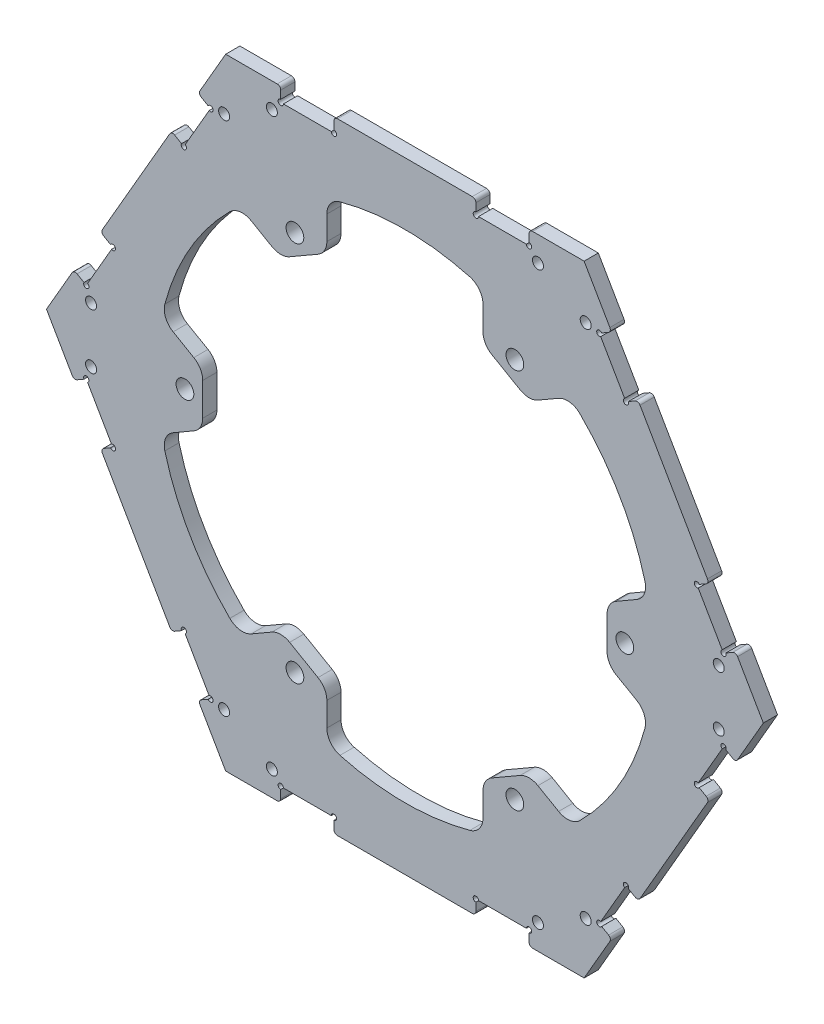
SolidWorks part; units mm, degrees
other "Markup1"
sketch "Sketch62" plane through (-128.5, -128.5, 146.8) normal (-0.0672, -0.6619, 0.7466) x (0.996, 0, 0.0896)
other "Markup2"
sketch "Sketch87" plane through (-128.5, 200.1498, -230) normal (-0.7911, 0.6051, -0.0891) x (-0.112, 0, 0.9937)
ref_plane "Front" through (0, 0, 0) normal (0, 0, 1) x (1, 0, 0)
ref_plane "Top" through (0, 0, 0) normal (0, 1, 0) x (1, 0, 0)
ref_plane "Right" through (0, 0, 0) normal (1, 0, 0) x (0, 0, -1)
sketch "Sketch80" plane through (0, 0, 0) normal (0, 0, -1) x (-1, 0, 0)
  line L0 (-68.551, 14.169) -> (-57, 7.5)
  line L1 (-57, 7.5) -> (-57, -7.5)
  line L2 (0, 0) -> (-81.4055, 0) construction
  line L3 (-68.551, -14.169) -> (-57, -7.5)
  line L4 (-22.0048, 66.4514) -> (-22.0048, 53.1134)
  line L5 (-22.0048, 53.1134) -> (-34.9952, 45.6134)
  line L7 (106.8098, 0) -> (53.4049, 92.5)
  line L8 (53.4049, 92.5) -> (-53.4049, 92.5)
  line L9 (-53.4049, 92.5) -> (-106.8098, 0)
  line L10 (-106.8098, 0) -> (-53.4049, -92.5)
  line L11 (-53.4049, -92.5) -> (53.4049, -92.5)
  line L18 (-46.5462, 52.2824) -> (-34.9952, 45.6134)
  line L19 (46.5462, 52.2824) -> (34.9952, 45.6134)
  line L20 (34.9952, 45.6134) -> (22.0048, 53.1134)
  line L21 (22.0048, 66.4514) -> (22.0048, 53.1134)
  line L22 (68.551, -14.169) -> (57, -7.5)
  line L23 (57, -7.5) -> (57, 7.5)
  line L24 (68.551, 14.169) -> (57, 7.5)
  line L25 (22.0048, -66.4514) -> (22.0048, -53.1134)
  line L26 (22.0048, -53.1134) -> (34.9952, -45.6134)
  line L27 (46.5462, -52.2824) -> (34.9952, -45.6134)
  line L28 (-46.5462, -52.2824) -> (-34.9952, -45.6134)
  line L29 (-34.9952, -45.6134) -> (-22.0048, -53.1134)
  line L30 (-22.0048, -66.4514) -> (-22.0048, -53.1134)
  line L31 (53.4049, -92.5) -> (106.8098, 0)
  arc A0 (-68.551, -14.169) -> (-46.5462, -52.2824) centre (0, 0) ccw
  arc A1 (-46.5462, 52.2824) -> (-68.551, 14.169) centre (0, 0) ccw
  arc A2 (22.0048, 66.4514) -> (-22.0048, 66.4514) centre (0, 0) ccw
  arc A3 (68.551, 14.169) -> (46.5462, 52.2824) centre (0, 0) ccw
  arc A4 (46.5462, -52.2824) -> (68.551, -14.169) centre (0, 0) ccw
  arc A5 (-22.0048, -66.4514) -> (22.0048, -66.4514) centre (0, 0) ccw
  circle A18 centre (0, 0) radius 92.5 construction
  circle A19 centre (-62, 0) radius 2.5
  circle A20 centre (-31, 53.6936) radius 2.5
  circle A21 centre (31, 53.6936) radius 2.5
  circle A22 centre (62, 0) radius 2.5
  circle A23 centre (31, -53.6936) radius 2.5
  circle A24 centre (-31, -53.6936) radius 2.5
  point P16 (-57, 0)
  point P47 (0, 0)
  dimension "D2" = 140
  dimension "D1" = 185
  dimension "D7" = 5
  dimension "D9" = 62
  dimension "D3" = 120
  dimension "D4" = 57
  dimension "D5" = 15
  dimension "D6" = 6
  dimension "D8" = 6
extrude "Boss-Extrude22" add sketch "Sketch80" along normal blind 4 separate body
sketch "Sketch88" plane through (0, 0, -4) normal (0, 0, -1) x (-1, 0, 0)
  line L0 (0, 0) -> (0, 96.9948) construction
  line L1 (20, 87.5) -> (35, 87.5)
  line L2 (20, 87.5) -> (20, 83.5)
  line L3 (20, 83.5) -> (35, 83.5)
  line L4 (35, 87.5) -> (35, 83.5)
  line L5 (-20, 83.5) -> (-35, 83.5)
  line L6 (-35, 87.5) -> (-35, 83.5)
  line L7 (-20, 87.5) -> (-35, 87.5)
  line L8 (-20, 87.5) -> (-20, 83.5)
  line L9 (62.3131, 59.0705) -> (54.8131, 72.0609)
  line L10 (58.2772, 74.0609) -> (54.8131, 72.0609)
  line L11 (65.7772, 61.0705) -> (58.2772, 74.0609)
  line L12 (65.7772, 61.0705) -> (62.3131, 59.0705)
  line L13 (85.7772, 26.4295) -> (82.3131, 24.4295)
  line L14 (85.7772, 26.4295) -> (93.2772, 13.4391)
  line L15 (93.2772, 13.4391) -> (89.8131, 11.4391)
  line L16 (82.3131, 24.4295) -> (89.8131, 11.4391)
  line L17 (82.3131, -24.4295) -> (89.8131, -11.4391)
  line L18 (93.2772, -13.4391) -> (89.8131, -11.4391)
  line L19 (85.7772, -26.4295) -> (93.2772, -13.4391)
  line L20 (85.7772, -26.4295) -> (82.3131, -24.4295)
  line L21 (65.7772, -61.0705) -> (62.3131, -59.0705)
  line L22 (65.7772, -61.0705) -> (58.2772, -74.0609)
  line L23 (58.2772, -74.0609) -> (54.8131, -72.0609)
  line L24 (62.3131, -59.0705) -> (54.8131, -72.0609)
  line L25 (20, -83.5) -> (35, -83.5)
  line L26 (35, -87.5) -> (35, -83.5)
  line L27 (20, -87.5) -> (35, -87.5)
  line L28 (20, -87.5) -> (20, -83.5)
  line L29 (-20, -87.5) -> (-20, -83.5)
  line L30 (-20, -87.5) -> (-35, -87.5)
  line L31 (-35, -87.5) -> (-35, -83.5)
  line L32 (-20, -83.5) -> (-35, -83.5)
  line L33 (-62.3131, -59.0705) -> (-54.8131, -72.0609)
  line L34 (-58.2772, -74.0609) -> (-54.8131, -72.0609)
  line L35 (-65.7772, -61.0705) -> (-58.2772, -74.0609)
  line L36 (-65.7772, -61.0705) -> (-62.3131, -59.0705)
  line L37 (-85.7772, -26.4295) -> (-82.3131, -24.4295)
  line L38 (-85.7772, -26.4295) -> (-93.2772, -13.4391)
  line L39 (-93.2772, -13.4391) -> (-89.8131, -11.4391)
  line L40 (-82.3131, -24.4295) -> (-89.8131, -11.4391)
  line L41 (-82.3131, 24.4295) -> (-89.8131, 11.4391)
  line L42 (-93.2772, 13.4391) -> (-89.8131, 11.4391)
  line L43 (-85.7772, 26.4295) -> (-93.2772, 13.4391)
  line L44 (-85.7772, 26.4295) -> (-82.3131, 24.4295)
  line L45 (-65.7772, 61.0705) -> (-62.3131, 59.0705)
  line L46 (-65.7772, 61.0705) -> (-58.2772, 74.0609)
  line L47 (-58.2772, 74.0609) -> (-54.8131, 72.0609)
  line L48 (-62.3131, 59.0705) -> (-54.8131, 72.0609)
  line L49 (-37.5, 80.5) -> (37.5, -80.5) construction
  circle A0 centre (-37.5, 80.5) radius 1.55
  circle A1 centre (37.5, 80.5) radius 1.55
  circle A4 centre (50.965, 72.726) radius 1.55
  circle A5 centre (88.465, 7.774) radius 1.55
  circle A6 centre (88.465, -7.774) radius 1.55
  circle A7 centre (50.965, -72.726) radius 1.55
  circle A8 centre (37.5, -80.5) radius 1.55
  circle A9 centre (-37.5, -80.5) radius 1.55
  circle A10 centre (-50.965, -72.726) radius 1.55
  circle A11 centre (-88.465, -7.774) radius 1.55
  circle A12 centre (-88.465, 7.774) radius 1.55
  circle A13 centre (-50.965, 72.726) radius 1.55
  point P7 (27.5, 87.5)
  point P54 (0, 0)
  point P57 (-27.5, 83.5)
  dimension "D6" = 3.1
  dimension "D7" = 10
  dimension "D8" = 3
  dimension "D9" = 6
  dimension "D1" = 15
  dimension "D2" = 4
  dimension "D3" = 87.5
  dimension "D4" = 55
  dimension "D5" = 6
extrude "Cut-Extrude1" cut sketch "Sketch88" against normal through all
sketch "Sketch89" plane through (0, 0, -4) normal (0, 0, -1) x (-1, 0, 0)
  line L0 (0, 0) -> (0, 109.644) construction
  circle A0 centre (-35, 83.5) radius 0.75
  circle A1 centre (-20, 83.5) radius 0.75
  circle A2 centre (20, 83.5) radius 0.75
  circle A3 centre (35, 83.5) radius 0.75
  circle A4 centre (54.8131, 72.0609) radius 0.75
  circle A5 centre (62.3131, 59.0705) radius 0.75
  circle A6 centre (82.3131, 24.4295) radius 0.75
  circle A7 centre (89.8131, 11.4391) radius 0.75
  circle A8 centre (89.8131, -11.4391) radius 0.75
  circle A9 centre (82.3131, -24.4295) radius 0.75
  circle A10 centre (62.3131, -59.0705) radius 0.75
  circle A11 centre (54.8131, -72.0609) radius 0.75
  circle A12 centre (35, -83.5) radius 0.75
  circle A13 centre (20, -83.5) radius 0.75
  circle A14 centre (-20, -83.5) radius 0.75
  circle A15 centre (-35, -83.5) radius 0.75
  circle A16 centre (-54.8131, -72.0609) radius 0.75
  circle A17 centre (-62.3131, -59.0705) radius 0.75
  circle A18 centre (-82.3131, -24.4295) radius 0.75
  circle A19 centre (-89.8131, -11.4391) radius 0.75
  circle A20 centre (-89.8131, 11.4391) radius 0.75
  circle A21 centre (-82.3131, 24.4295) radius 0.75
  circle A22 centre (-62.3131, 59.0705) radius 0.75
  circle A23 centre (-54.8131, 72.0609) radius 0.75
  dimension "D1" = 1.5
  dimension "D2" = 6
extrude "Cut-Extrude2" cut sketch "Sketch89" against normal through all
sketch "Sketch90" plane through (0, 0, -4) normal (0, 0, -1) x (-1, 0, 0)
  line L0 (50.5181, -87.5) -> (101.0363, 0)
  line L1 (101.0363, 0) -> (50.5181, 87.5)
  line L2 (50.5181, 87.5) -> (-50.5181, 87.5)
  line L3 (-50.5181, 87.5) -> (-101.0363, 0)
  line L4 (-101.0363, 0) -> (-50.5181, -87.5)
  line L5 (-50.5181, -87.5) -> (50.5181, -87.5)
  line L6 (53.4049, -92.5) -> (106.8098, 0)
  line L7 (106.8098, 0) -> (53.4049, 92.5)
  line L8 (53.4049, 92.5) -> (-53.4049, 92.5)
  line L9 (-53.4049, 92.5) -> (-106.8098, 0)
  line L10 (-106.8098, 0) -> (-53.4049, -92.5)
  line L11 (-53.4049, -92.5) -> (53.4049, -92.5)
  line L12 (53.4049, -92.5) -> (106.8098, 0)
  line L13 (106.8098, 0) -> (53.4049, 92.5)
  line L14 (53.4049, 92.5) -> (-53.4049, 92.5)
  line L15 (-53.4049, 92.5) -> (-106.8098, 0)
  line L16 (-106.8098, 0) -> (-53.4049, -92.5)
  line L17 (-53.4049, -92.5) -> (53.4049, -92.5)
  dimension "D1" = 0
  dimension "D2" = 5
extrude "Cut-Extrude6" cut sketch "Sketch90" against normal through all contours L16 L17 L12 L13 L14 L15 L5 L4 L3 L2 L1 L0
fillet "Fillet1" radius 1 24 edges at (-35, 87.5, -2) (-20, 87.5, -2) (20, 87.5, -2) (35, 87.5, -2) (85.7772, 26.4295, -2) (93.2772, 13.4391, -2) (65.7772, 61.0705, -2) (58.2772, 74.0609, -2) (65.7772, -61.0705, -2) (58.2772, -74.0609, -2) (85.7772, -26.4295, -2) (93.2772, -13.4391, -2) (-20, -87.5, -2) (-35, -87.5, -2) (20, -87.5, -2) (35, -87.5, -2) (-85.7772, -26.4295, -2) (-93.2772, -13.4391, -2) (-65.7772, -61.0705, -2) (-58.2772, -74.0609, -2) (-85.7772, 26.4295, -2) (-93.2772, 13.4391, -2) (-65.7772, 61.0705, -2) (-58.2772, 74.0609, -2)
fillet "Fillet2" radius 5 24 edges at (57, 7.5, -2) (57, -7.5, -2) (68.551, -14.169, -2) (46.5462, -52.2824, -2) (34.9952, -45.6134, -2) (22.0048, -53.1134, -2) (22.0048, -66.4514, -2) (-22.0048, -66.4514, -2) (-22.0048, -53.1134, -2) (-34.9952, -45.6134, -2) (-46.5462, -52.2824, -2) (-68.551, -14.169, -2) (-57, -7.5, -2) (-57, 7.5, -2) (-68.551, 14.169, -2) (-46.5462, 52.2824, -2) (-34.9952, 45.6134, -2) (-22.0048, 53.1134, -2) (22.0048, 66.4514, -2) (22.0048, 53.1134, -2) (34.9952, 45.6134, -2) (46.5462, 52.2824, -2) (68.551, 14.169, -2) (-22.0048, 66.4514, -2)
